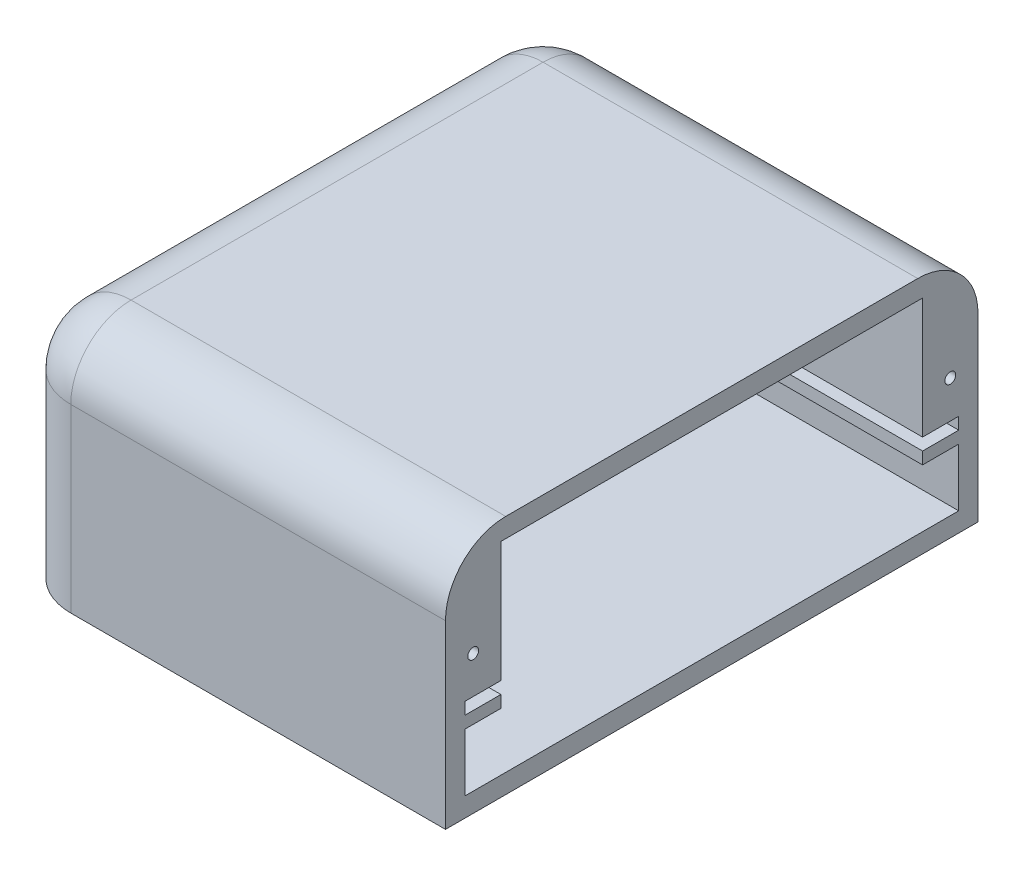
SolidWorks part; units mm, degrees
ref_plane "Front Plane" through (0, 0, 0) normal (0, 0, 1) x (1, 0, 0)
ref_plane "Top Plane" through (0, 0, 0) normal (0, 1, 0) x (1, 0, 0)
ref_plane "Right Plane" through (0, 0, 0) normal (1, 0, 0) x (0, 0, -1)
sketch "Sketch1" plane through (0, 0, 0) normal (0, 1, 0) x (1, 0, 0)
  line L1 (0, 0) -> (72.2, 0)
  line L2 (0, 0) -> (0, 88.4)
  line L3 (0, 88.4) -> (72.2, 88.4)
  line L4 (72.2, 0) -> (72.2, 88.4)
  dimension "D1" = 72.2
  dimension "D2" = 88.4
extrude "Boss-Extrude1" add sketch "Sketch1" along normal blind 40
sketch "Sketch2" plane through (72.2, 0, 0) normal (1, 0, 0) x (0, 0, -1)
  line L0 (0, 40) -> (0, 0) construction
  line L1 (3.2, 3.2) -> (85.2, 3.2)
  line L2 (3.2, 3.2) -> (3.2, 36.8)
  line L3 (3.2, 36.8) -> (85.2, 36.8)
  line L4 (85.2, 3.2) -> (85.2, 36.8)
  line L5 (0, 40) -> (88.4, 40) construction
  line L6 (88.4, 40) -> (88.4, 0) construction
  line L7 (0, 0) -> (88.4, 0) construction
  line L8 (44.2, 36.8) -> (44.2, 15.884)
  line L9 (3.2, 36.8) -> (9.2, 36.8)
  line L10 (3.2, 36.8) -> (3.2, 16.8)
  line L11 (3.2, 16.8) -> (9.2, 16.8)
  line L12 (9.2, 36.8) -> (9.2, 16.8)
  line L13 (3.2, 14.8) -> (9.2, 14.8)
  line L14 (3.2, 14.8) -> (3.2, 12.8)
  line L15 (3.2, 12.8) -> (9.2, 12.8)
  line L16 (9.2, 14.8) -> (9.2, 12.8)
  line L17 (85.2, 12.8) -> (79.2, 12.8)
  line L18 (79.2, 14.8) -> (79.2, 12.8)
  line L19 (85.2, 14.8) -> (79.2, 14.8)
  line L20 (85.2, 14.8) -> (85.2, 12.8)
  line L21 (85.2, 16.8) -> (79.2, 16.8)
  line L22 (79.2, 36.8) -> (79.2, 16.8)
  line L23 (85.2, 36.8) -> (79.2, 36.8)
  line L24 (85.2, 36.8) -> (85.2, 16.8)
  dimension "D1" = 3.2
  dimension "D2" = 3.2
  dimension "D3" = 3.2
  dimension "D4" = 3.2
  dimension "D5" = 20
  dimension "D6" = 6
  dimension "D7" = 2
  dimension "D8" = 2
extrude "Cut-Extrude4" cut sketch "Sketch2" against normal blind 69
fillet "Fillet1" radius 10 5 edges at (0, 20, 0) (0, 20, -88.4) (36.1, 40, 0) (0, 40, -44.2) (36.1, 40, -88.4)
sketch "Sketch3" plane through (72.2, 0, 0) normal (1, 0, 0) x (0, 0, -1)
  line L0 (9.2, 36.8) -> (9.2, 16.8) construction
  line L3 (0, 30) -> (0, 0) construction
  line L4 (44.2, 36.8) -> (44.2, 25.8584)
  line L5 (9.2, 36.8) -> (79.2, 36.8) construction
  circle A0 centre (4.6, 23) radius 0.9
  circle A1 centre (83.8, 23) radius 0.9
  point P6 (0, 15)
  dimension "D1" = 4.6
  dimension "D2" = 8
extrude "Cut-Extrude5" cut sketch "Sketch3" against normal blind 20 contours A0 | A1
